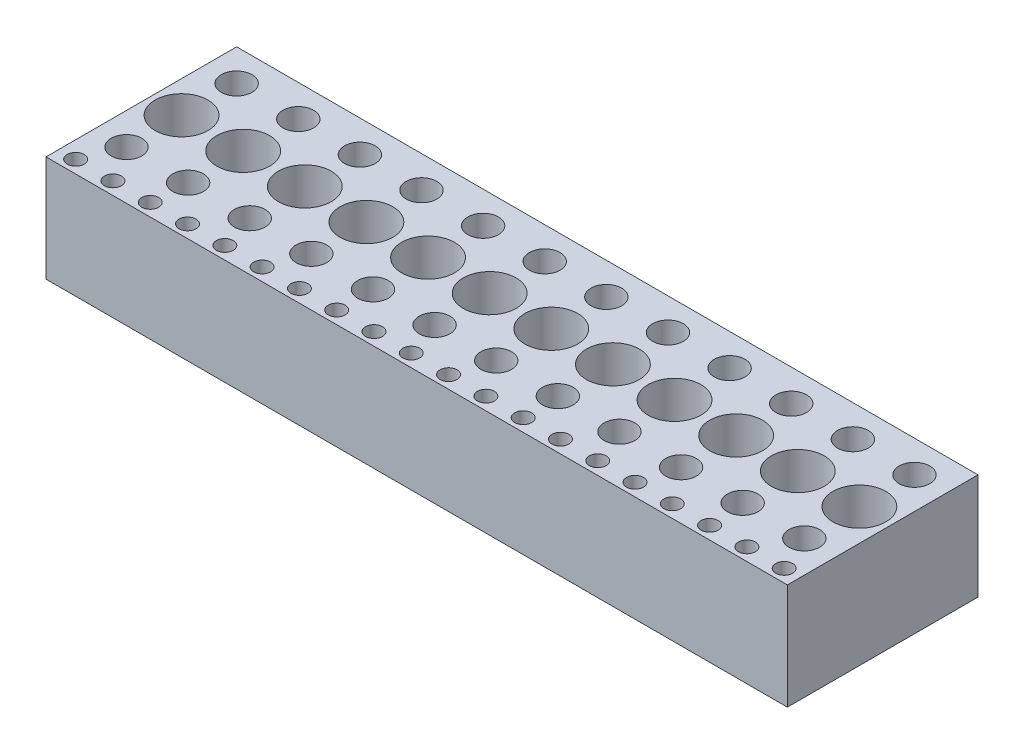
SolidWorks part; units mm, degrees
ref_plane "前视基准面" through (0, 0, 0) normal (0, 0, 1) x (1, 0, 0)
ref_plane "上视基准面" through (0, 0, 0) normal (0, 1, 0) x (1, 0, 0)
ref_plane "右视基准面" through (0, 0, 0) normal (1, 0, 0) x (0, 0, -1)
other "Configuration Table"
sketch "草图1" plane through (0, 0, 0) normal (0, 1, 0) x (1, 0, 0)
  line L1 (-17.5, 4.5) -> (17.5, 4.5)
  line L2 (-17.5, 4.5) -> (-17.5, -4.5)
  line L3 (-17.5, -4.5) -> (17.5, -4.5)
  line L4 (17.5, 4.5) -> (17.5, -4.5)
  line L5 (-17.5, 4.5) -> (17.5, -4.5) construction
  line L6 (-17.5, -4.5) -> (17.5, 4.5) construction
  point P0 (0, 0)
  dimension "D1" = 35
  dimension "D2" = 9
extrude "凸台-拉伸1" add sketch "草图1" along normal blind 5
sketch "草图2" plane through (0, 5, 0) normal (0, 1, 0) x (1, 0, 0)
  line L5 (17.5, -4.5) -> (17.5, 4.5) construction
  line L42 (-17.5, -4.5) -> (17.5, -4.5) construction
  line L43 (-17.5, 4.5) -> (-17.5, -4.5) construction
  line L60 (17.5, 4.5) -> (-17.5, 4.5) construction
  circle A0 centre (-16, 3) radius 0.725
  circle A1 centre (-13.0909, 3) radius 0.725
  circle A2 centre (-10.1818, 3) radius 0.725
  circle A3 centre (-7.2727, 3) radius 0.725
  circle A4 centre (-4.3636, 3) radius 0.725
  circle A5 centre (-1.4545, 3) radius 0.725
  circle A6 centre (1.4545, 3) radius 0.725
  circle A7 centre (4.3636, 3) radius 0.725
  circle A8 centre (7.2727, 3) radius 0.725
  circle A9 centre (10.1818, 3) radius 0.725
  circle A10 centre (13.0909, 3) radius 0.725
  circle A11 centre (16, 3) radius 0.725
  circle A12 centre (-16, 0.4) radius 1.25
  circle A13 centre (-13.0909, 0.4) radius 1.25
  circle A14 centre (-10.1818, 0.4) radius 1.25
  circle A15 centre (-7.2727, 0.4) radius 1.25
  circle A16 centre (-4.3636, 0.4) radius 1.25
  circle A17 centre (-1.4545, 0.4) radius 1.25
  circle A18 centre (1.4545, 0.4) radius 1.25
  circle A19 centre (4.3636, 0.4) radius 1.25
  circle A20 centre (7.2727, 0.4) radius 1.25
  circle A21 centre (10.1818, 0.4) radius 1.25
  circle A22 centre (13.0909, 0.4) radius 1.25
  circle A23 centre (16, 0.4) radius 1.25
  circle A24 centre (-16, -2.2) radius 0.725
  circle A25 centre (-13.0909, -2.2) radius 0.725
  circle A26 centre (-10.1818, -2.2) radius 0.725
  circle A27 centre (-7.2727, -2.2) radius 0.725
  circle A28 centre (-4.3636, -2.2) radius 0.725
  circle A29 centre (-1.4545, -2.2) radius 0.725
  circle A30 centre (1.4545, -2.2) radius 0.725
  circle A31 centre (4.3636, -2.2) radius 0.725
  circle A32 centre (7.2727, -2.2) radius 0.725
  circle A33 centre (10.1818, -2.2) radius 0.725
  circle A34 centre (13.0909, -2.2) radius 0.725
  circle A35 centre (16, -2.2) radius 0.725
  circle A36 centre (-16.7, -3.9) radius 0.4
  circle A37 centre (-14.9395, -3.9) radius 0.4
  circle A38 centre (-13.1789, -3.9) radius 0.4
  circle A39 centre (-11.4184, -3.9) radius 0.4
  circle A40 centre (-9.6579, -3.9) radius 0.4
  circle A41 centre (-7.8974, -3.9) radius 0.4
  circle A42 centre (-6.1368, -3.9) radius 0.4
  circle A43 centre (-4.3763, -3.9) radius 0.4
  circle A44 centre (-2.6158, -3.9) radius 0.4
  circle A45 centre (-0.8553, -3.9) radius 0.4
  circle A46 centre (0.9053, -3.9) radius 0.4
  circle A47 centre (2.6658, -3.9) radius 0.4
  circle A48 centre (4.4263, -3.9) radius 0.4
  circle A49 centre (6.1868, -3.9) radius 0.4
  circle A50 centre (7.9474, -3.9) radius 0.4
  circle A51 centre (9.7079, -3.9) radius 0.4
  circle A52 centre (11.4684, -3.9) radius 0.4
  circle A53 centre (13.2289, -3.9) radius 0.4
  circle A54 centre (14.9895, -3.9) radius 0.4
  circle A55 centre (16.75, -3.9) radius 0.4
  dimension "D1" = 1.45
  dimension "D5" = 2.5
  dimension "D8" = 1.45
  dimension "D14" = 0.8
  dimension "D2" = 1.5
  dimension "D3" = 1.5
  dimension "D4" = 1.5
  dimension "D6" = 2.6
  dimension "D7" = 2.9091
  dimension "D9" = 2.6
  dimension "D10" = 1.5
  dimension "D11" = 1.5
  dimension "D12" = 0.6
  dimension "D13" = 0.8
  dimension "D15" = 0.75
extrude "切除-拉伸1" cut sketch "草图2" against normal through all
